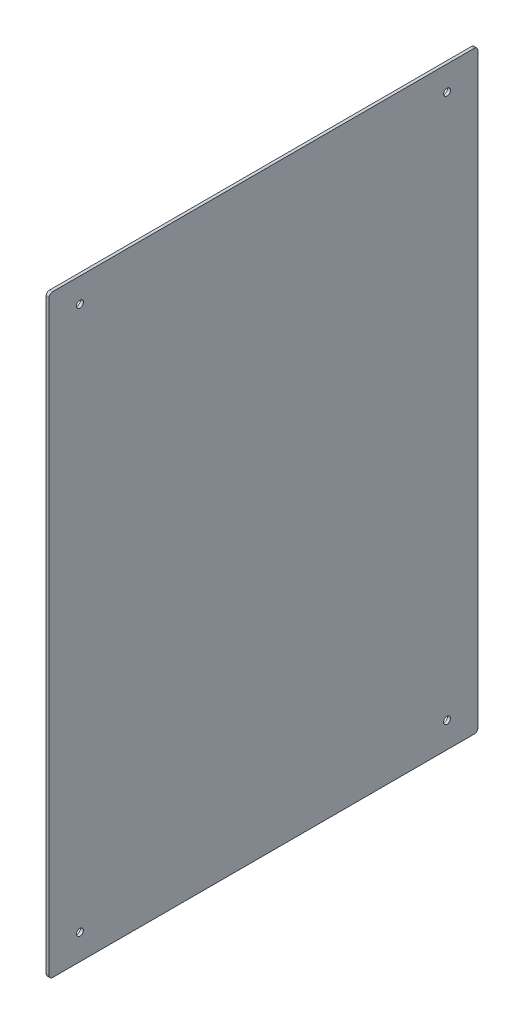
SolidWorks part; units mm, degrees
ref_plane "前视基准面" through (0, 0, 0) normal (0, 0, 1) x (1, 0, 0)
ref_plane "上视基准面" through (0, 0, 0) normal (0, 1, 0) x (1, 0, 0)
ref_plane "右视基准面" through (0, 0, 0) normal (1, 0, 0) x (0, 0, -1)
sketch "草图1" plane through (0, 0, 0) normal (1, 0, 0) x (0, 0, -1)
  line L1 (0, 0) -> (188, 0)
  line L2 (0, 0) -> (0, 260.5)
  line L3 (0, 260.5) -> (188, 260.5)
  line L4 (188, 0) -> (188, 260.5)
  circle A0 centre (174.5, 249.8) radius 1.5
  circle A1 centre (174.5, 11.2) radius 1.5
  circle A2 centre (13.5, 249.8) radius 1.5
  circle A3 centre (13.5, 11.2) radius 1.5
  dimension "D7" = 3
  dimension "D1" = 260.5
  dimension "D2" = 188
  dimension "D3" = 13.5
  dimension "D4" = 10.7
  dimension "D5" = 11.2
  dimension "D6" = 13.5
extrude "凸台-拉伸2" add sketch "草图1" along normal blind 1.3
fillet "圆角1" radius 1.5 4 edges at (0.65, 0, -188) (0.65, 0, 0) (0.65, 260.5, 0) (0.65, 260.5, -188)
